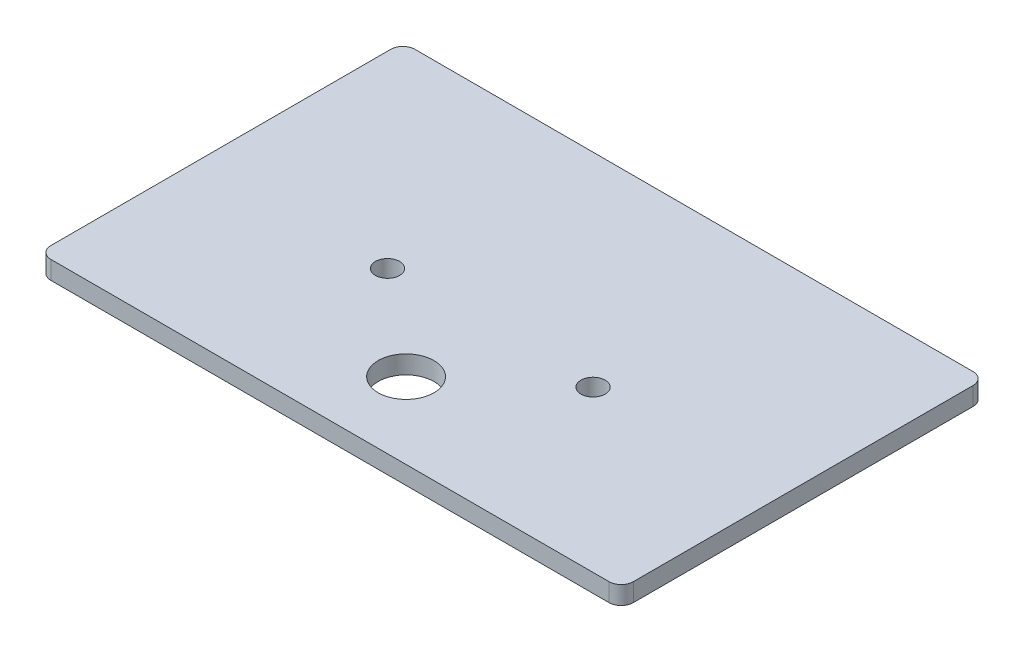
SolidWorks part; units mm, degrees
ref_plane "Front Plane" through (0, 0, 0) normal (0, 0, 1) x (1, 0, 0)
ref_plane "Top Plane" through (0, 0, 0) normal (0, 1, 0) x (1, 0, 0)
ref_plane "Right Plane" through (0, 0, 0) normal (1, 0, 0) x (0, 0, -1)
sketch "Sketch1" plane through (0, 0, 0) normal (0, 1, 0) x (1, 0, 0)
  line L1 (-36, -22.5) -> (36, -22.5)
  line L2 (-36, -22.5) -> (-36, 22.5)
  line L3 (-36, 22.5) -> (36, 22.5)
  line L4 (36, -22.5) -> (36, 22.5)
  line L5 (-36, -22.5) -> (36, 22.5) construction
  line L6 (-36, 22.5) -> (36, -22.5) construction
  point P0 (0, 0)
  dimension "D1" = 45
  dimension "D2" = 72
extrude "Boss-Extrude1" add sketch "Sketch1" along normal blind 2.25
fillet "Fillet2" radius 1.5 1 edges at (-36, 1.125, -22.5)
fillet "Fillet3" radius 1.5 3 edges at (36, 1.125, -22.5) (36, 1.125, 22.5) (-36, 1.125, 22.5)
sketch "Sketch16" plane through (0, 2.25, 0) normal (0, 1, 0) x (1, 0, 0)
  circle A0 centre (0, -13.0973) radius 3.45
  dimension "D1" = 6.9
extrude "Cut-Extrude1" cut sketch "Sketch16" against normal blind 10
sketch "Sketch18" plane through (0, 2.25, 0) normal (0, 1, 0) x (1, 0, 0)
  circle A1 centre (-12.7349, -2.6569) radius 1.5
  circle A2 centre (12.6823, -2.6569) radius 1.5
  dimension "D1" = 3
  dimension "D2" = 3
extrude "Cut-Extrude2" cut sketch "Sketch18" against normal blind 10
